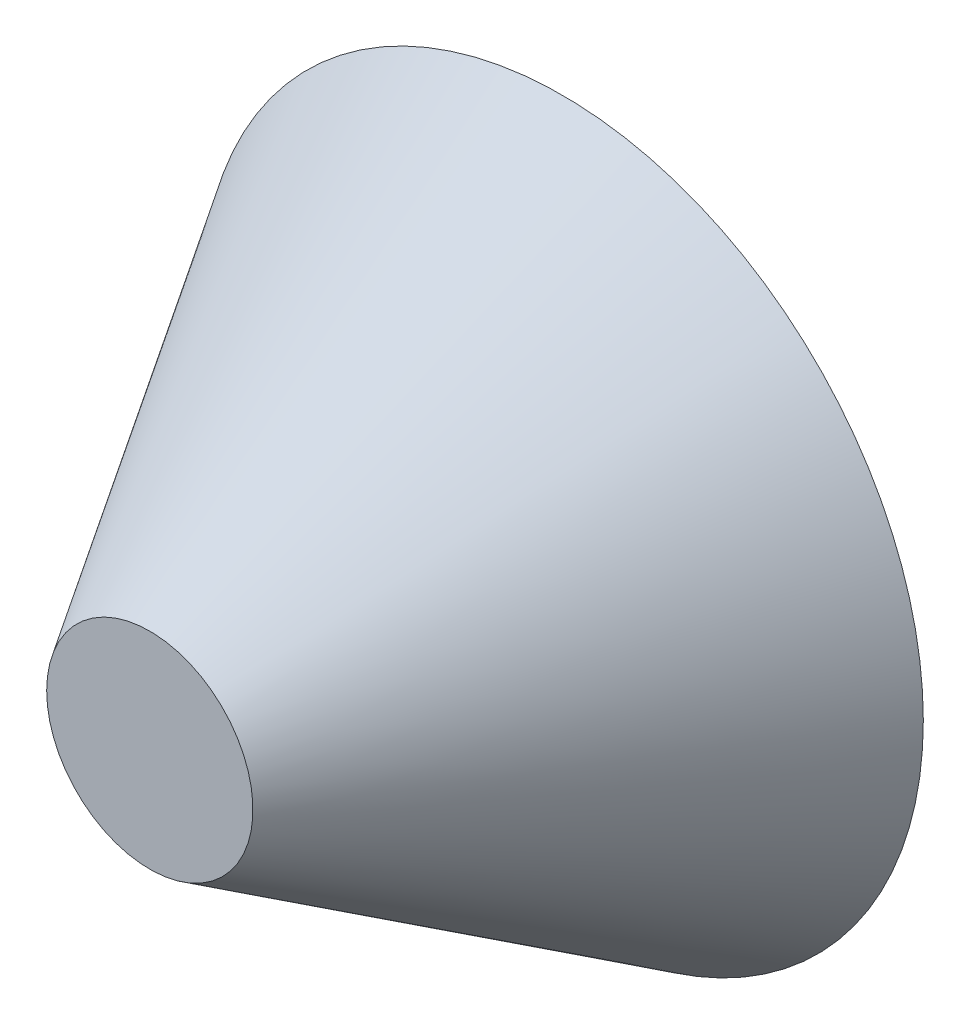
SolidWorks part; units mm, degrees
ref_plane "Front Plane" through (0, 0, 0) normal (0, 0, 1) x (1, 0, 0)
ref_plane "Top Plane" through (0, 0, 0) normal (0, 1, 0) x (1, 0, 0)
ref_plane "Right Plane" through (0, 0, 0) normal (1, 0, 0) x (0, 0, -1)
sketch "Sketch1" plane through (0, 0, 0) normal (0, 0, 1) x (1, 0, 0)
  circle A0 centre (0, 0) radius 444.5
  dimension "D1" = 889
ref_plane "Plane1" through (0, 0, 508) normal (0, 0, 1) x (1, 0, 0)
sketch "Sketch2" plane through (0, 0, 508) normal (0, 0, 1) x (1, 0, 0)
  circle A0 centre (0, 0) radius 127
  dimension "D1" = 254
loft "Loft1" add profiles "Sketch1", "Sketch2"
